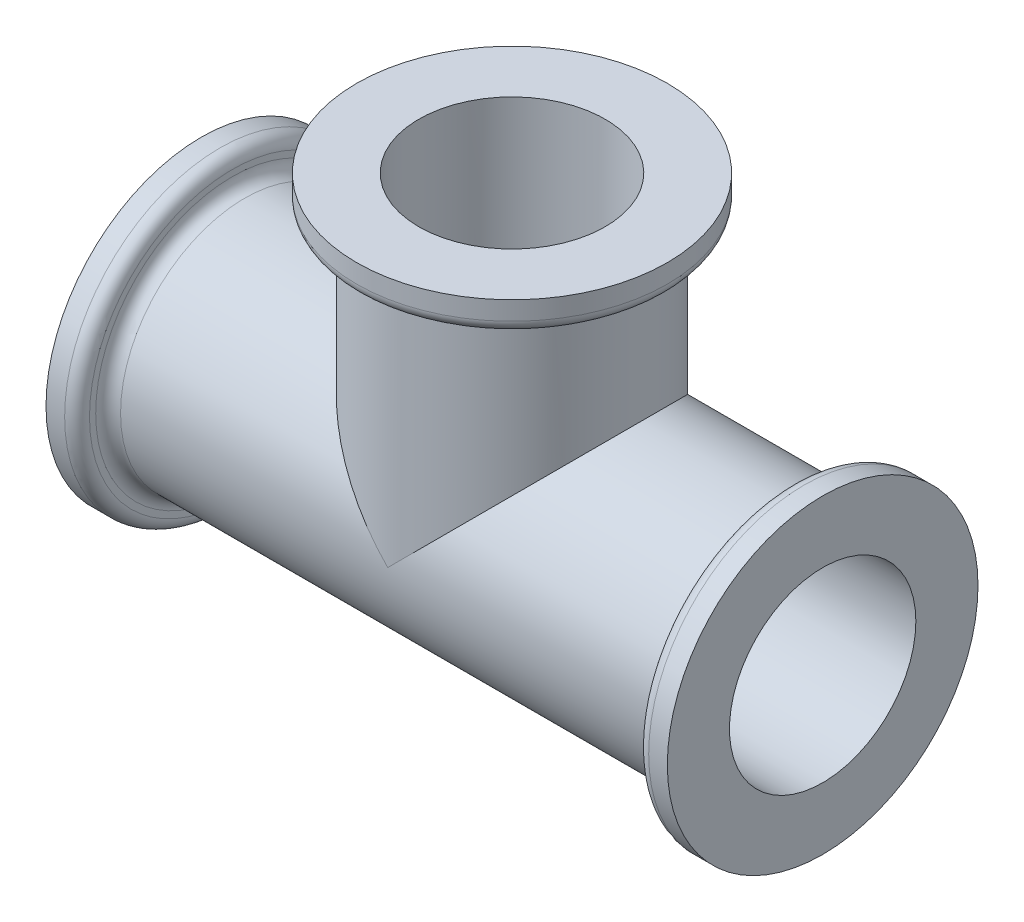
SolidWorks part; units mm, degrees
material "Thornel VCB-20 Carbon Cloth"
ref_plane "Front Plane" through (0, 0, 0) normal (0, 0, 1) x (1, 0, 0)
ref_plane "Top Plane" through (0, 0, 0) normal (0, 1, 0) x (1, 0, 0)
ref_plane "Right Plane" through (0, 0, 0) normal (1, 0, 0) x (0, 0, -1)
sketch "Sketch1" plane through (0, 0, 0) normal (0, 0, 1) x (1, 0, 0)
  line L0 (-25, 0) -> (0, 0)
  line L2 (0, 0) -> (25, 0)
  point P7 (12.9412, -1.5749)
  dimension "D1" = 25
  dimension "D2" = 25
sketch "Sketch2" plane through (0, 0, 0) normal (1, 0, 0) x (0, 0, -1)
  circle A0 centre (0, 0) radius 7.5
  dimension "D1" = 15
sweep "Sweep-Thin1" add profiles "Sketch2" path "Sketch1" parameters "D1"=2.5
sketch "Sketch3" plane through (25, 0, 0) normal (1, 0, 0) x (0, 0, -1)
  circle A0 centre (0, 0) radius 12.5
  circle A1 centre (0, 0) radius 7.5 construction
  circle A3 centre (0, 0) radius 7.5
  dimension "D2" = 25
extrude "Boss-Extrude1" add sketch "Sketch3" against normal blind 2.5
mirror "Mirror1" about plane through (0, 0, 0) normal (1, 0, 0) of bodies 102
ref_plane "Plane1" through (0, 7.5, 0) normal (0, 1, 0) x (1, 0, 0)
sketch "Sketch4" plane through (0, 7.5, 0) normal (0, 1, 0) x (1, 0, 0)
  circle A0 centre (0, 0) radius 7.5
  circle A1 centre (0, 0) radius 10
  dimension "D1" = 15
  dimension "D2" = 20
extrude "Boss-Extrude2" add sketch "Sketch4" along normal blind 15 and the other way blind 7.5
sketch "Sketch5" plane through (25, 0, 0) normal (1, 0, 0) x (0, 0, -1)
  circle A0 centre (0, 0) radius 7.5 construction
  circle A3 centre (0, 0) radius 7.5
extrude "Cut-Extrude1" cut sketch "Sketch5" against normal through all
sketch "Sketch6" plane through (0, 22.5, 0) normal (0, 1, 0) x (1, 0, 0)
  circle A0 centre (0, 0) radius 7.5 construction
  circle A1 centre (0, 0) radius 7.5
extrude "Cut-Extrude2" cut sketch "Sketch6" against normal up to next
sketch "Sketch7" plane through (0, 22.5, 0) normal (0, 1, 0) x (1, 0, 0)
  circle A0 centre (0, 0) radius 12.5
  circle A1 centre (0, 0) radius 7.5 construction
  circle A2 centre (0, 0) radius 7.5
  dimension "D1" = 25
extrude "Boss-Extrude3" add sketch "Sketch7" against normal blind 2.5
fillet "Fillet1" radius 1 6 edges at (-22.5, 0, -12.5) (-22.5, 0, 10) (22.5, 0, -12.5) (22.5, 0, -10) (0, 20, 10) (0, 20, 12.5)
